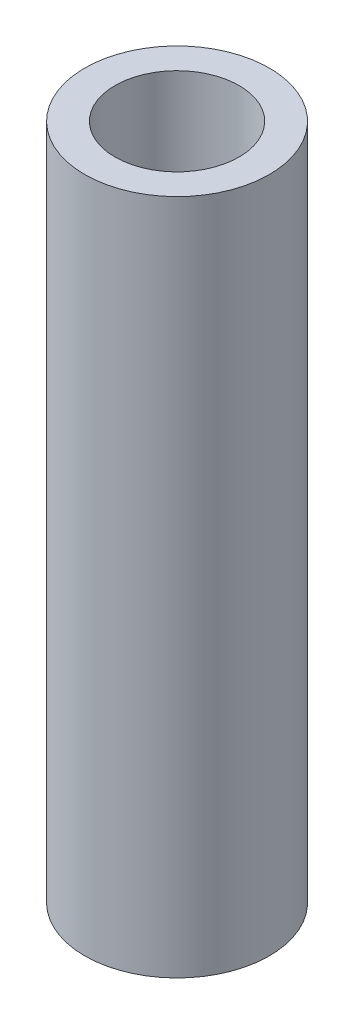
SolidWorks part; units mm, degrees
material "6061 Alloy"
ref_plane "Front Plane" through (0, 0, 0) normal (0, 0, 1) x (1, 0, 0)
ref_plane "Top Plane" through (0, 0, 0) normal (0, 1, 0) x (1, 0, 0)
ref_plane "Right Plane" through (0, 0, 0) normal (1, 0, 0) x (0, 0, -1)
sketch "Sketch1" plane through (0, 0, 0) normal (0, 1, 0) x (1, 0, 0)
  circle A0 centre (0, 0) radius 4.7625
  dimension "D1" = 9.525
extrude "Boss-Extrude1" add sketch "Sketch1" along normal blind 34.925
hole_wizard "M6 Clearance Hole1" positions "Sketch3" profile "Sketch2" hole size "M6" standard "ANSI Metric" end condition up to next
sketch "Sketch3" plane through (0, 34.925, 0) normal (0, 1, 0) x (1, 0, 0)
  point P0 (0, 0)
sketch "Sketch2" plane through (0, 34.925, 0) normal (1, 0, 0) x (0, 0, 1)
  line L0 (0, 0) -> (0, 34.925)
  line L1 (0, 34.925) -> (3.2, 34.925)
  line L2 (3.2, 34.925) -> (3.2, 0)
  line L5 (3.2, 0) -> (0, 0)
  line L11 (0, -6.35) -> (0, 107.95) construction
  dimension "Thru Hole Dia." = 6.4
  dimension "Thru Hole Depth" = 34.925
